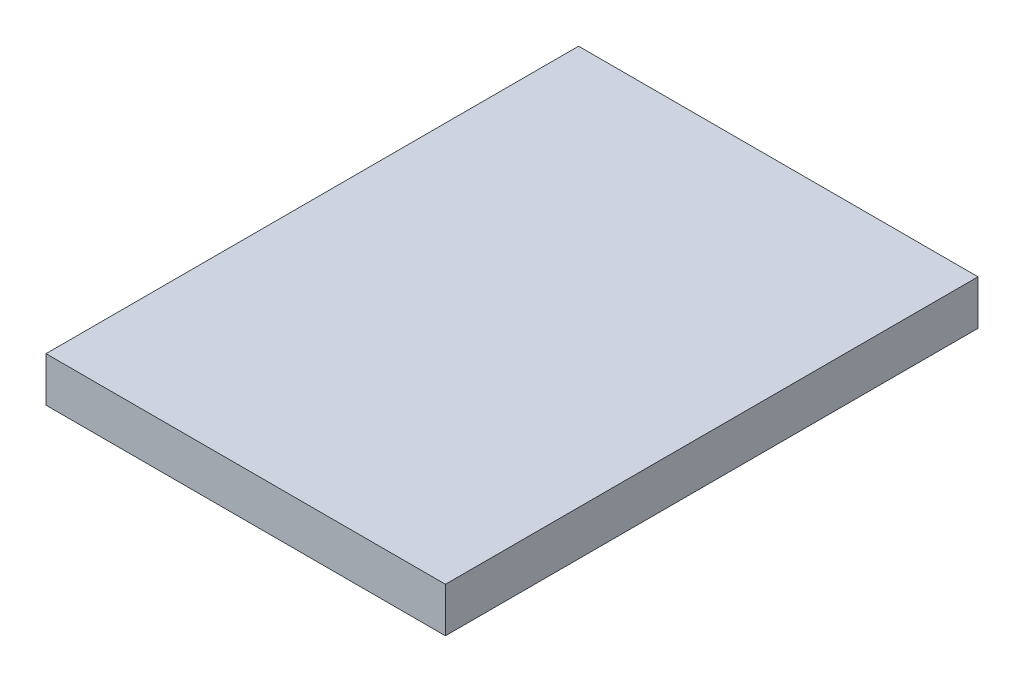
SolidWorks part; units mm, degrees
ref_plane "Front Plane" through (0, 0, 0) normal (0, 0, 1) x (1, 0, 0)
ref_plane "Top Plane" through (0, 0, 0) normal (0, 1, 0) x (1, 0, 0)
ref_plane "Right Plane" through (0, 0, 0) normal (1, 0, 0) x (0, 0, -1)
sketch "Sketch1" plane through (0, 0, 0) normal (0, 1, 0) x (1, 0, 0)
  line L1 (0, 0) -> (51, 0)
  line L2 (0, 0) -> (0, 68)
  line L3 (0, 68) -> (51, 68)
  line L4 (51, 0) -> (51, 68)
  dimension "D1" = 51
  dimension "D2" = 68
extrude "Boss-Extrude1" add sketch "Sketch1" along normal blind 5.7
